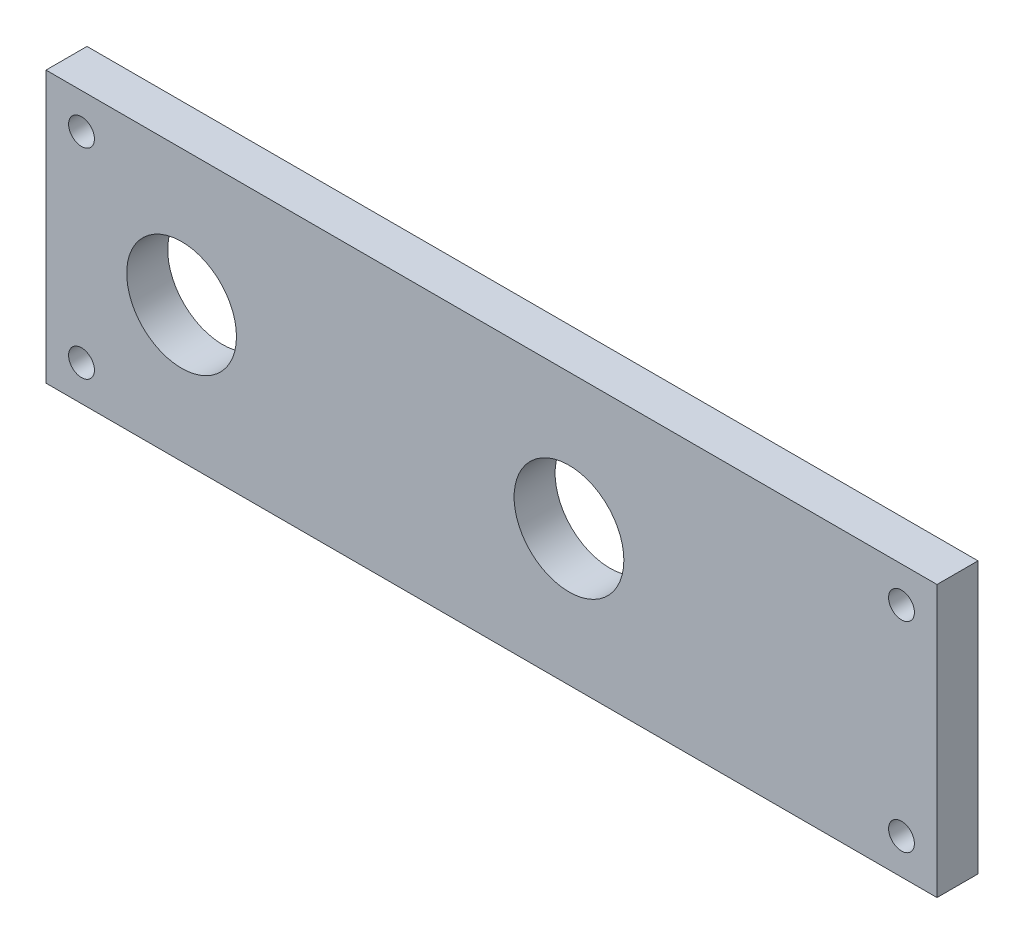
SolidWorks part; units mm, degrees
ref_plane "Front Plane" through (0, 0, 0) normal (0, 0, 1) x (1, 0, 0)
ref_plane "Top Plane" through (0, 0, 0) normal (0, 1, 0) x (1, 0, 0)
ref_plane "Right Plane" through (0, 0, 0) normal (1, 0, 0) x (0, 0, -1)
sketch "Sketch1" plane through (0, 0, 0) normal (0, 0, 1) x (1, 0, 0)
  line L0 (0, 0) -> (60, 0) construction
  line L3 (-15.5, 21) -> (-15.5, 15.5) construction
  line L8 (-21, 21) -> (21, 21)
  line L9 (-21, 21) -> (-21, -21)
  line L10 (-21, -21) -> (21, -21)
  line L11 (21, 21) -> (21, -21)
  line L12 (-21, 21) -> (21, -21) construction
  line L13 (-21, -21) -> (21, 21) construction
  line L14 (-15.5, 15.5) -> (-21, 15.5) construction
  circle A0 centre (0, 0) radius 17 construction
  circle A1 centre (60, 0) radius 47 construction
  circle A2 centre (0, 0) radius 15
  circle A3 centre (60, 0) radius 45
  circle A6 centre (-15.5, 15.5) radius 2
  circle A7 centre (15.5, 15.5) radius 2
  circle A8 centre (-15.5, -15.5) radius 2
  circle A9 centre (15.5, -15.5) radius 2
  circle A10 centre (0, 0) radius 8.5
  circle A11 centre (60, 0) radius 8.5
  dimension "D1" = 34
  dimension "D2" = 94
  dimension "D3" = 30
  dimension "D4" = 90
  dimension "D5" = 17
  dimension "D9" = 4
  dimension "D7" = 42
  dimension "D8" = 31
sketch "Sketch2" plane through (0, 0, 0) normal (0, 0, 1) x (1, 0, 0)
  line L0 (-21, -21) -> (21, -21) construction
  line L1 (-21, 21) -> (117, 21)
  line L2 (-21, 21) -> (-21, -21)
  line L3 (-21, -21) -> (117, -21)
  line L4 (117, 21) -> (117, -21)
  circle A1 centre (15.5, -15.5) radius 2 construction
  circle A2 centre (-15.5, -15.5) radius 2 construction
  circle A3 centre (15.5, 15.5) radius 2 construction
  circle A4 centre (-15.5, 15.5) radius 2 construction
  circle A5 centre (15.5, -15.5) radius 2 construction
  circle A6 centre (-15.5, -15.5) radius 2
  circle A7 centre (15.5, 15.5) radius 2 construction
  circle A8 centre (-15.5, 15.5) radius 2
  circle A12 centre (111.5, 15.5) radius 2
  circle A13 centre (111.5, -15.5) radius 2
  circle A14 centre (60, 0) radius 47 construction
  circle A15 centre (111.5, -15.5) radius 3.175 construction
  circle A16 centre (-15.5, 15.5) radius 3.175 construction
  circle A17 centre (0, 0) radius 8.5 construction
  circle A18 centre (0, 0) radius 8.5
  circle A19 centre (60, 0) radius 8.5 construction
  circle A20 centre (60, 0) radius 8.5
  dimension "D1" = 10
  dimension "D2" = 5.5
  dimension "D3" = 6.35
extrude "Boss-Extrude1" add sketch "Sketch2" along normal mid plane 6.35
